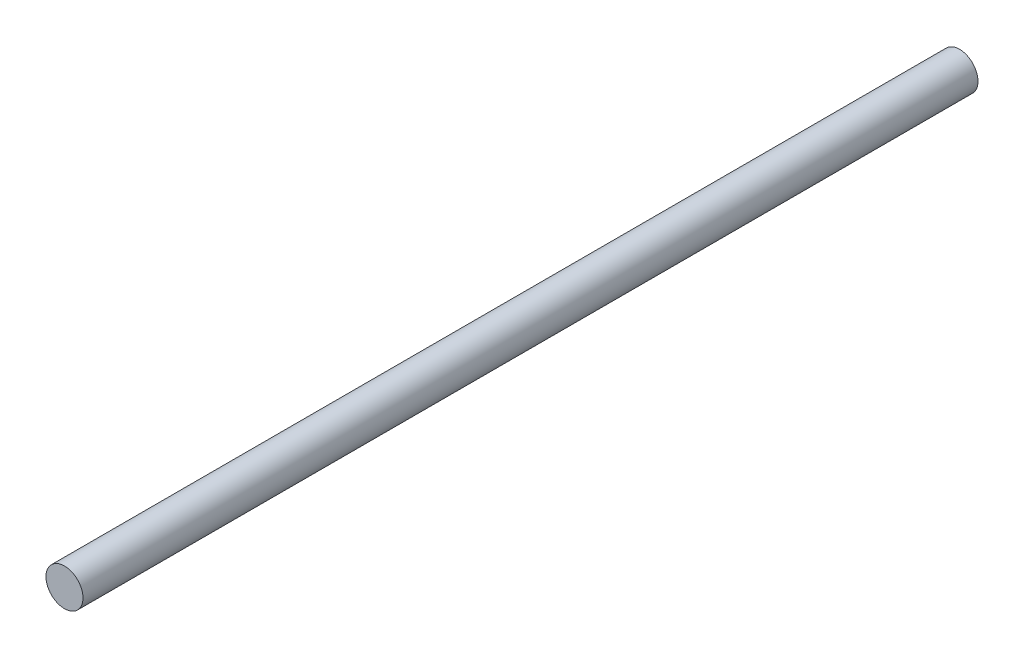
SolidWorks part; units mm, degrees
ref_plane "Front Plane" through (0, 0, 0) normal (0, 0, 1) x (1, 0, 0)
ref_plane "Top Plane" through (0, 0, 0) normal (0, 1, 0) x (1, 0, 0)
ref_plane "Right Plane" through (0, 0, 0) normal (1, 0, 0) x (0, 0, -1)
sketch "Esquisse1" plane through (0, 0, 0) normal (0, 0, 1) x (1, 0, 0)
  circle A0 centre (0, 0) radius 3
  dimension "D1" = 6
extrude "Boss.-Extru.1" add sketch "Esquisse1" along normal blind 145
